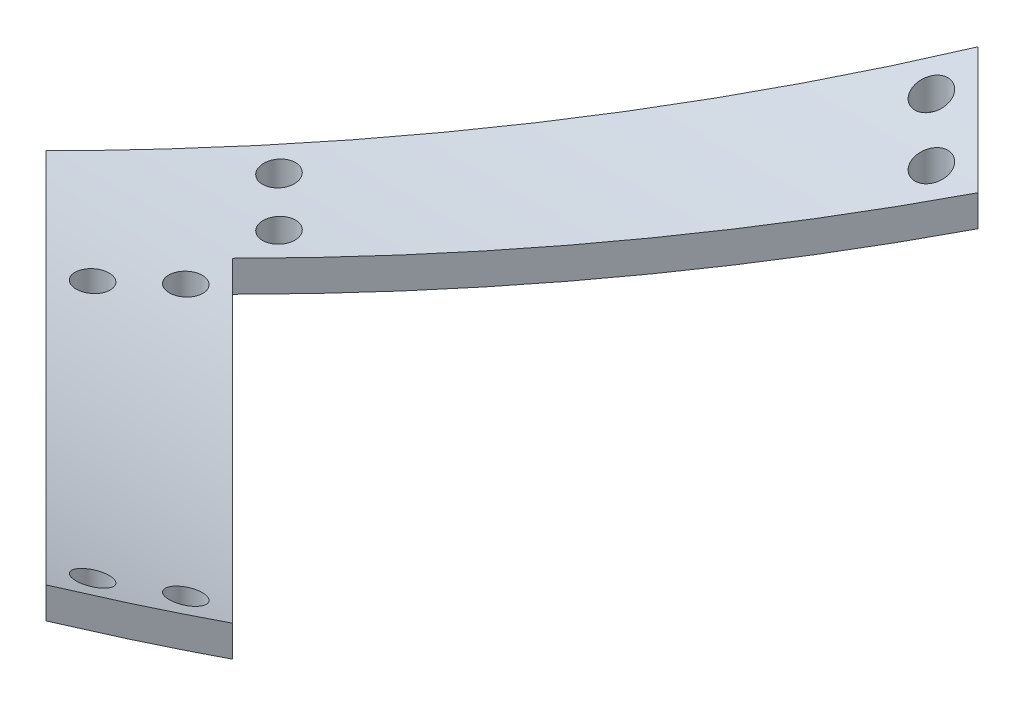
SolidWorks part; units mm, degrees
ref_plane "Front Plane" through (0, 0, 0) normal (0, 0, 1) x (1, 0, 0)
ref_plane "Top Plane" through (0, 0, 0) normal (0, 1, 0) x (1, 0, 0)
ref_plane "Right Plane" through (0, 0, 0) normal (1, 0, 0) x (0, 0, -1)
sketch "Sketch3" plane through (0, 0, 0) normal (1, 0, 0) x (0, 0, -1)
  line L0 (-8.3933, 1.9614) -> (-8.3933, -4.052)
  line L6 (-8.3933, -4.3886) -> (-8.3933, 1.9614)
  line L8 (232.9067, -4.3886) -> (232.9067, 1.9614)
  line L9 (232.9067, -4.052) -> (232.9067, 1.9614)
  arc A2 (-8.3933, 1.9614) -> (232.9067, 1.9614) centre (112.2567, 210.9333) ccw
  arc A3 (-8.3933, -4.052) -> (232.9067, -4.052) centre (112.2567, 204.9199) ccw
  dimension "D1" = 6.35
  dimension "D2" = 241.3
extrude "Boss-Extrude4" add sketch "Sketch3" along normal blind 304.8 contours L0 A3 L8 A2
ref_plane "Plane1" through (0, 1.9614, 0) normal (0, 1, 0) x (1, 0, 0)
sketch "Sketch4" plane through (0, 1.9614, 0) normal (0, 1, 0) x (1, 0, 0)
  line L4 (123.3168, 202.0592) -> (33.5143, 112.2567)
  line L13 (123.3168, 22.4542) -> (141.2773, 40.4147)
  line L14 (69.4353, 112.2567) -> (141.2773, 184.0987)
  line L15 (141.2773, 184.0987) -> (123.3168, 202.0592)
  line L16 (141.2773, 40.4147) -> (69.4353, 112.2567)
  line L17 (123.3168, 22.4542) -> (33.5143, 112.2567)
  point P0 (0, 0)
  point P19 (50.8, 172.5817)
extrude "Cut-Extrude2" cut sketch "Sketch4" against normal blind 150 flip side to cut
sketch "Sketch6" plane through (0, 1.9614, 0) normal (0, 1, 0) x (1, 0, 0)
  circle A0 centre (123.3168, 193.079) radius 3.175
  circle A1 centre (132.2971, 184.0987) radius 3.175
  circle A2 centre (60.4551, 130.2173) radius 3.175
  circle A3 centre (69.4353, 121.237) radius 3.175
  circle A4 centre (132.2969, 40.4145) radius 3.175
  circle A5 centre (123.3166, 31.4343) radius 3.175
  circle A6 centre (60.455, 94.2962) radius 3.175
  circle A7 centre (69.4353, 103.2764) radius 3.175
  point P0 (0, 0)
  point P20 (0, 0)
  point P21 (0, 0)
extrude "Cut-Extrude3" cut sketch "Sketch6" against normal blind 150
